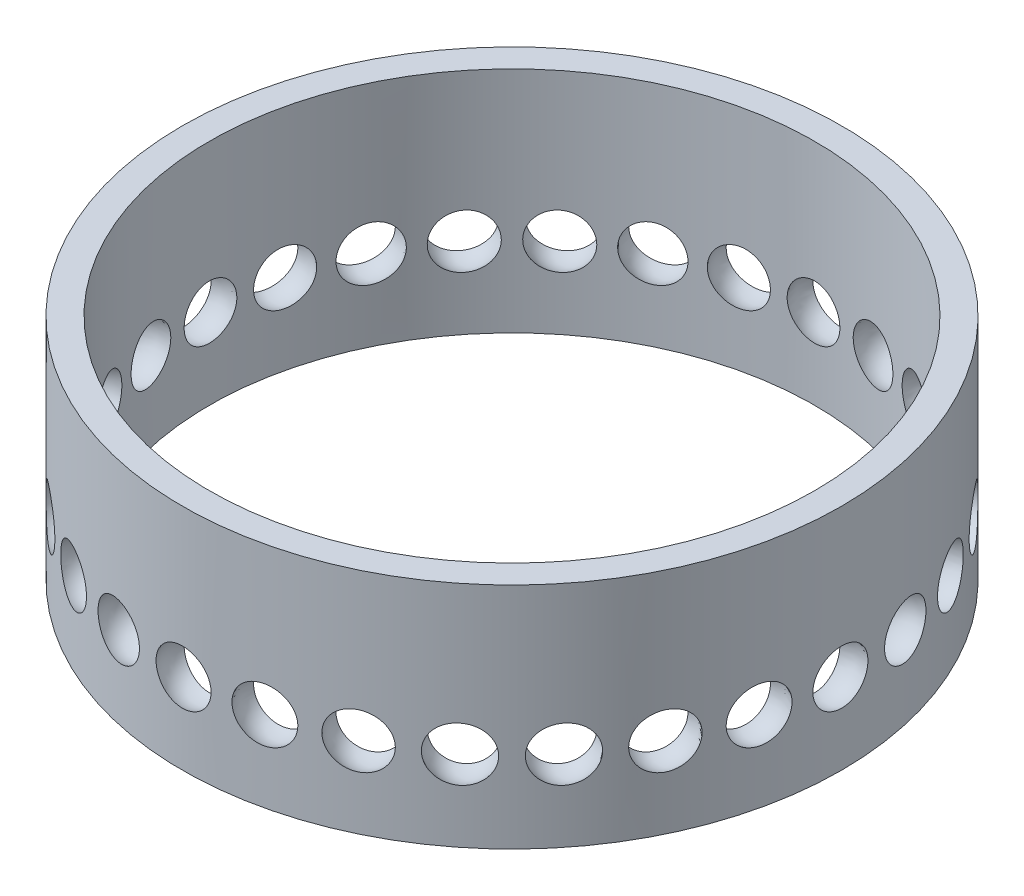
SolidWorks part; units mm, degrees
ref_plane "Front Plane" through (0, 0, 0) normal (0, 0, 1) x (1, 0, 0)
ref_plane "Top Plane" through (0, 0, 0) normal (0, 1, 0) x (1, 0, 0)
ref_plane "Right Plane" through (0, 0, 0) normal (1, 0, 0) x (0, 0, -1)
sketch "Sketch1" plane through (0, 0, 0) normal (0, 1, 0) x (1, 0, 0)
  circle A0 centre (0, 0) radius 11.75
  dimension "D1" = 23.5
extrude "Extrude-Thin1" add sketch "Sketch1" along normal blind 8.5 from offset 3 thin offset against normal yes
sketch "Sketch2" plane through (0, 0, 0) normal (0, 0, 1) x (1, 0, 0)
  line L0 (11.75, -1.12) -> (11.75, 1.12)
  line L2 (11.75, 0) -> (-11.75, 0) construction
  arc A0 (11.75, 1.12) -> (11.75, -1.12) centre (11.75, 0) cw
  dimension "D1" = 1.12
revolve "Cut-Revolve1" cut sketch "Sketch2" angle 360 about L0
pattern_circular "CirPattern1" count 28 over 360 about axis through (0, 0, 0) along (0, 1, 0) of "Cut-Revolve1"
